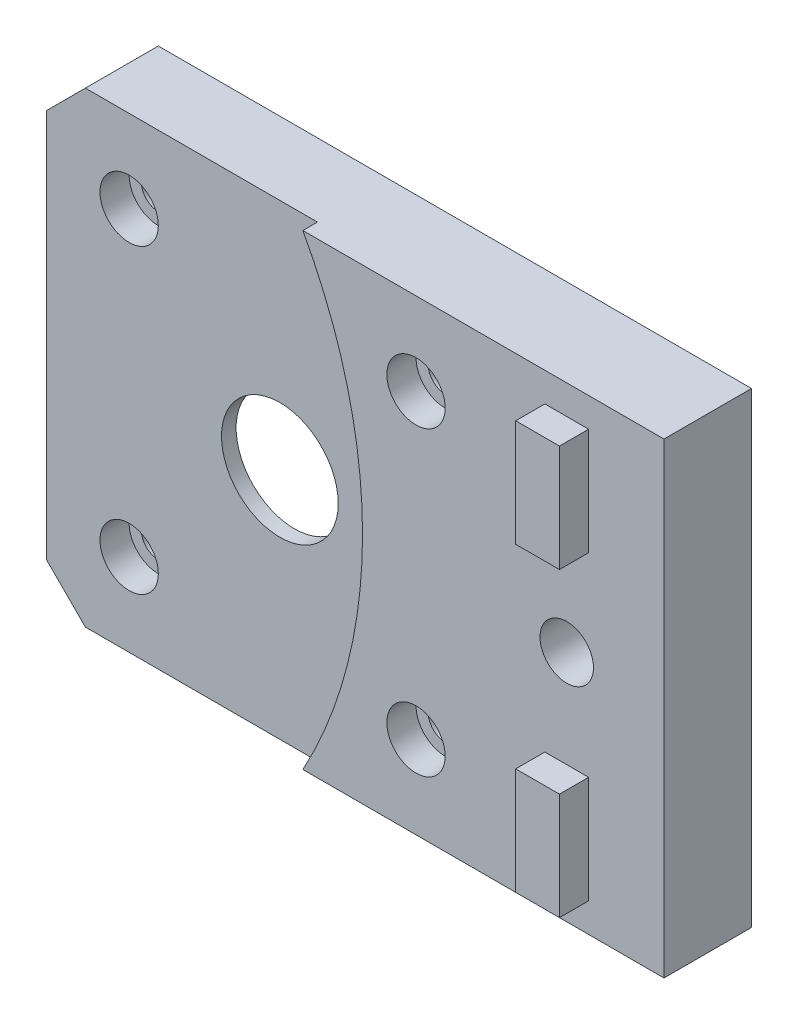
SolidWorks part; units mm, degrees
ref_plane "Front Plane" through (0, 0, 0) normal (0, 0, 1) x (1, 0, 0)
ref_plane "Top Plane" through (0, 0, 0) normal (0, 1, 0) x (1, 0, 0)
ref_plane "Right Plane" through (0, 0, 0) normal (1, 0, 0) x (0, 0, -1)
sketch "Sketch1" plane through (0, 0, 0) normal (0, 0, 1) x (1, 0, 0)
  line L1 (-21, -21) -> (21, -21)
  line L2 (-21, -21) -> (-21, 21)
  line L3 (-21, 21) -> (21, 21)
  line L4 (21, -21) -> (21, 21)
  line L5 (-21, -21) -> (21, 21) construction
  line L6 (-21, 21) -> (21, -21) construction
  line L7 (21, 21) -> (41, 21)
  line L8 (21, 21) -> (21, -21)
  line L9 (21, -21) -> (41, -21)
  line L10 (41, 21) -> (41, -21)
  point P0 (0, 0)
  dimension "D1" = 42
  dimension "D2" = 42
  dimension "D3" = 20
extrude "Boss-Extrude1" add sketch "Sketch1" along normal blind 6 contours L10 L7 L4 L9 | L1 L4 L3 L2
sketch "Sketch2" plane through (0, 0, 0) normal (0, 0, 1) x (1, 0, 0)
  circle A0 centre (0, 0) radius 11.25
  dimension "D1" = 22.5
extrude "Cut-Extrude1" cut sketch "Sketch2" along normal blind 3
sketch "Sketch3" plane through (0, 0, 0) normal (0, 0, 1) x (1, 0, 0)
  line L1 (21, -21) -> (-21, -21)
  line L2 (21, -21) -> (21, 21)
  line L3 (21, 21) -> (-21, 21)
  line L4 (-21, -21) -> (-21, 21)
  line L5 (21, -21) -> (-21, 21) construction
  line L6 (21, 21) -> (-21, -21) construction
  circle A0 centre (-15.4998, 15.4998) radius 1.75
  circle A1 centre (0, 0) radius 6
  circle A2 centre (15.4998, 15.4998) radius 1.75
  circle A3 centre (15.4998, -15.4998) radius 1.75
  circle A4 centre (-15.4998, -15.4998) radius 1.75
  point P0 (0, 0)
  point P18 (0, 0)
  point P19 (0, 0)
  point P20 (0, 0)
  point P21 (0, 0)
  dimension "D1" = 3.5
  dimension "D2" = 3.5
  dimension "D3" = 3.5
  dimension "D4" = 3.5
  dimension "D5" = 12
  dimension "D6" = 21.92
  dimension "D7" = 21.92
  dimension "D8" = 21.92
  dimension "D9" = 21.92
extrude "Cut-Extrude2" cut sketch "Sketch3" along normal through all both and the other way through all contours A2 | A1 | A0 | A4 | A3
sketch "Sketch4" plane through (0, 0, 6) normal (0, 0, 1) x (1, 0, 0)
  circle A0 centre (15.4998, 15.4998) radius 1.75 construction
  circle A1 centre (-15.4998, 15.4998) radius 1.75 construction
  circle A2 centre (15.4998, -15.4998) radius 1.75 construction
  circle A3 centre (-15.4998, -15.4998) radius 1.75 construction
  circle A4 centre (15.4998, 15.4998) radius 1.75
  circle A5 centre (-15.4998, 15.4998) radius 1.75
  circle A6 centre (15.4998, -15.4998) radius 1.75
  circle A7 centre (-15.4998, -15.4998) radius 1.75
  circle A8 centre (-15.4998, -15.4998) radius 3
  circle A9 centre (-15.4998, 15.4998) radius 3
  circle A10 centre (15.4998, 15.4998) radius 3
  circle A11 centre (15.4998, -15.4998) radius 3
  dimension "D1" = 6
  dimension "D2" = 6
  dimension "D3" = 6
  dimension "D4" = 6
extrude "Cut-Extrude3" cut sketch "Sketch4" against normal blind 3
sketch "Sketch5" plane through (0, 0, 6) normal (0, 0, 1) x (1, 0, 0)
  line L0 (-21, 21) -> (41, 21) construction
  line L1 (33.25, -21) -> (28.75, -21)
  line L2 (33.25, -21) -> (33.25, 21)
  line L3 (33.25, 21) -> (28.75, 21)
  line L4 (28.75, -21) -> (28.75, 21)
  line L5 (33.25, -21) -> (28.75, 21) construction
  line L6 (33.25, 21) -> (28.75, -21) construction
  line L7 (41, 21) -> (41, -21) construction
  point P0 (31, 0)
  dimension "D1" = 10
  dimension "D2" = 4.5
extrude "Boss-Extrude2" add sketch "Sketch5" along normal blind 3
chamfer "Chamfer1" distance 3 angle 45 2 edges at (-21, 21, 3) (-21, -21, 3)
sketch "Sketch6" plane through (0, 0, 0) normal (0, 0, -1) x (-1, 0, 0)
  line L0 (-41, 21) -> (-41, -21) construction
  circle A0 centre (-31, 0) radius 2.75
  dimension "D1" = 5.5
  dimension "D2" = 10
extrude "Cut-Extrude4" cut sketch "Sketch6" against normal through all both and the other way through all
sketch "Sketch7" plane through (0, 0, 6) normal (0, 0, 1) x (1, 0, 0)
  line L1 (35.7282, -10) -> (26.2718, -10)
  line L2 (35.7282, -10) -> (35.7282, 10)
  line L3 (35.7282, 10) -> (26.2718, 10)
  line L4 (26.2718, -10) -> (26.2718, 10)
  line L5 (35.7282, -10) -> (26.2718, 10) construction
  line L6 (35.7282, 10) -> (26.2718, -10) construction
  circle A0 centre (31, 0) radius 2.75 construction
  circle A1 centre (31, 0) radius 2.75
  dimension "D1" = 20
extrude "Cut-Extrude5" cut sketch "Sketch7" along normal through all
sketch "Sketch8" plane through (0, 0, 0) normal (0, 0, -1) x (-1, 0, 0)
  line L0 (-21, -21) -> (-21, 21)
  line L1 (24, -24) -> (-41, -24)
  line L2 (24, -24) -> (24, 24)
  line L3 (24, 24) -> (-41, 24)
  line L4 (-41, -24) -> (-41, 24)
  line L6 (21, -18) -> (21, 18)
  line L7 (21, 18) -> (18, 21)
  line L8 (18, 21) -> (-41, 21)
  line L9 (-41, 21) -> (-41, -21)
  line L10 (-41, -21) -> (18, -21)
  line L11 (18, -21) -> (21, -18)
  line L12 (21, -18) -> (21, 18)
  line L13 (21, 18) -> (18, 21)
  line L14 (18, 21) -> (-41, 21)
  line L15 (-41, 21) -> (-41, -21)
  line L16 (-41, -21) -> (18, -21)
  line L17 (18, -21) -> (21, -18)
  line L18 (-21, 21) -> (-41, 21)
  line L19 (-21, 21) -> (-21, -21)
  line L20 (-21, -21) -> (-41, -21)
  line L21 (-41, 21) -> (-41, -21)
  line L22 (-41, -21) -> (-21, -21)
  line L23 (-41, -21) -> (-41, 21)
  line L24 (-41, 21) -> (-21, 21)
  line L25 (-21, -21) -> (-21, 21)
  circle A0 centre (-31, 0) radius 2.75 construction
  circle A1 centre (-31, 0) radius 2.75
  circle A2 centre (-31, 0) radius 7
  line M18 (21, -18) -> (21, 18)
  line M19 (21, 18) -> (18, 21)
  line M20 (18, 21) -> (-41, 21)
  line M21 (-41, 21) -> (-41, -21)
  line M22 (-41, -21) -> (18, -21)
  line M23 (18, -21) -> (21, -18)
  dimension "D6" = 14
  dimension "D2" = 3
  dimension "D3" = 3
  dimension "D4" = 3
  dimension "D5" = 20
  dimension "D1" = 0
extrude "Boss-Extrude4" add sketch "Sketch8" along normal blind 3 and the other way blind 6 contours L4 L1 L2 L3 M20 M19 M18 M23 M22 | L0 A2 M22 M20 M21
chamfer "Chamfer2" distance 4 angle 45 2 edges at (-24, -24, 1.5) (-24, 24, 1.5)
sketch "Sketch9" plane through (0, 0, 6) normal (0, 0, 1) x (1, 0, 0)
  circle A0 centre (-40, 0) radius 50
  dimension "D2" = 100
  dimension "D1" = 40
extrude "Cut-Extrude7" cut sketch "Sketch9" against normal blind 1.5 contours A0
sketch "Sketch10" plane through (0, 0, 3) normal (0, 0, 1) x (1, 0, 0)
  circle A0 centre (-15.4998, 15.4998) radius 3 construction
  circle A1 centre (-15.4998, -15.4998) radius 3 construction
  circle A2 centre (-15.4998, 15.4998) radius 3
  circle A3 centre (-15.4998, -15.4998) radius 3
extrude "Cut-Extrude8" cut sketch "Sketch10" against normal blind 1.5
